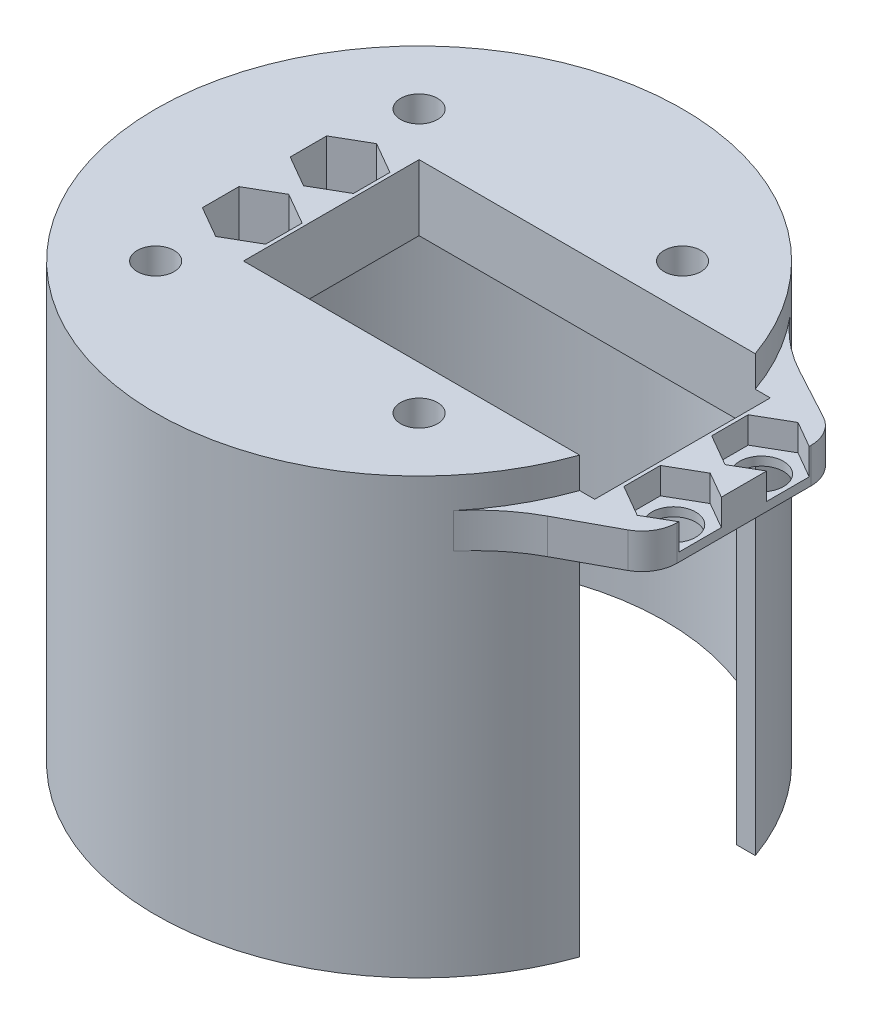
SolidWorks part; units mm, degrees
ref_plane "前视基准面" through (0, 0, 0) normal (0, 0, 1) x (1, 0, 0)
ref_plane "上视基准面" through (0, 0, 0) normal (0, 1, 0) x (1, 0, 0)
ref_plane "右视基准面" through (0, 0, 0) normal (1, 0, 0) x (0, 0, -1)
sketch "草图1" plane through (0, 0, 0) normal (0, 1, 0) x (1, 0, 0)
  line L0 (18.9568, 14.3477) -> (24.9021, 11.134)
  line L5 (-20, 10) -> (20, 10)
  line L6 (-20, 10) -> (-20, -10)
  line L11 (-20, -10) -> (20, -10)
  line L12 (20, 10) -> (20, -10)
  line L13 (-20, 10) -> (20, -10) construction
  line L14 (-20, -10) -> (20, 10) construction
  line L15 (-20, 10) -> (20, 10)
  line L17 (-27, -10) -> (20, -10)
  line L18 (27, 7.6152) -> (27, -7.6152)
  line L19 (-27, 10) -> (27, -10) construction
  line L20 (-27, -10) -> (27, 10) construction
  line L21 (-24, 5) -> (-21.5, 5)
  line L22 (-24, 5) -> (-24, 2.5)
  line L23 (-24, -5) -> (-21.5, -5)
  line L24 (24, 5) -> (24, -5)
  line L25 (-24, 5) -> (24, -5) construction
  line L26 (-24, -5) -> (-21.5525, -4.4901) construction
  line L27 (24.9021, -11.134) -> (18.9568, -14.3477)
  line L28 (21.5, 5) -> (24, 5)
  line L29 (21.5, -5) -> (24, -5)
  line L30 (-20, 5) -> (20, 5)
  line L31 (-24, -2.5) -> (-24, -5)
  line L32 (-20, -5) -> (20, -5)
  line L33 (-20, -4.1667) -> (24, 5) construction
  circle A0 centre (-10, 0) radius 10
  arc A1 (13.0803, 19.1651) -> (13.0803, -19.1651) centre (-10, 0) ccw
  circle A2 centre (24, 5) radius 2.5
  circle A3 centre (24, -5) radius 2.5
  circle A4 centre (-24, 5) radius 2.5
  circle A5 centre (-24, -5) radius 2.5
  arc A7 (18.2843, -10) -> (18.2843, 10) centre (-10, 0) ccw
  arc A8 (18.9568, -14.3477) -> (13.0803, -19.1651) centre (28.4671, -31.9418) ccw
  arc A9 (18.9568, 14.3477) -> (13.0803, 19.1651) centre (28.4671, 31.9418) cw
  arc A10 (24.9021, 11.134) -> (27, 7.6152) centre (23, 7.6152) cw
  arc A11 (24.9021, -11.134) -> (27, -7.6152) centre (23, -7.6152) ccw
  point P0 (0, 0)
  point P5 (-10, 0)
  point P9 (0, 0)
  point P14 (0, 0)
  dimension "D3" = 20
  dimension "D2" = 10
  dimension "D4" = 4
  dimension "D1" = 10
extrude "凸台-拉伸3" add sketch "草图1" along normal blind 4
sketch "草图10" plane through (0, 0, 0) normal (0, -1, 0) x (1, 0, 0)
  line L1 (20, 10) -> (-20, 10)
  line L2 (20, 10) -> (20, -10)
  line L3 (20, -10) -> (-20, -10)
  line L4 (-20, 10) -> (-20, -10)
  line L5 (20, 10) -> (-20, -10) construction
  line L6 (20, -10) -> (-20, 10) construction
  circle A0 centre (-10, 0) radius 30
  circle A1 centre (-10, 0) radius 28
  point P4 (0, 0)
  arc M35 (13.0803, 19.1651) -> (13.0803, -19.1651) centre (-10, 0) ccw
extrude "凸台-拉伸16" add sketch "草图10" along normal blind 42 contours A1 L1 A0 L3 M35
sketch "草图2" plane through (0, 4, 0) normal (0, 1, 0) x (1, 0, 0)
  line L0 (24, 0.8431) -> (27.6, 2.9215)
  line L1 (-24, 0.8431) -> (-20.4, 2.9215)
  line L2 (-20.4, 2.9215) -> (-20.4, 7.0785)
  line L3 (-20.4, 7.0785) -> (-24, 9.1569)
  line L4 (-24, 9.1569) -> (-27.6, 7.0785)
  line L5 (-27.6, 7.0785) -> (-27.6, 2.9215)
  line L6 (-27.6, 2.9215) -> (-24, 0.8431)
  line L7 (27.6, 2.9215) -> (27.6, 7.0785)
  line L8 (27.6, 7.0785) -> (24, 9.1569)
  line L9 (24, 9.1569) -> (20.4, 7.0785)
  line L10 (20.4, 7.0785) -> (20.4, 2.9215)
  line L11 (20.4, 2.9215) -> (24, 0.8431)
  line L12 (24, -9.1569) -> (27.6, -7.0785)
  line L13 (27.6, -7.0785) -> (27.6, -2.9215)
  line L14 (27.6, -2.9215) -> (24, -0.8431)
  line L15 (24, -0.8431) -> (20.4, -2.9215)
  line L16 (20.4, -2.9215) -> (20.4, -7.0785)
  line L17 (20.4, -7.0785) -> (24, -9.1569)
  line L18 (-24, -9.1569) -> (-20.4, -7.0785)
  line L19 (-20.4, -7.0785) -> (-20.4, -2.9215)
  line L20 (-20.4, -2.9215) -> (-24, -0.8431)
  line L21 (-24, -0.8431) -> (-27.6, -2.9215)
  line L22 (-27.6, -2.9215) -> (-27.6, -7.0785)
  line L23 (-27.6, -7.0785) -> (-24, -9.1569)
  circle A0 centre (-24, 5) radius 3.6 construction
  dimension "D1" = 2
  dimension "D2" = 2
extrude "切除-拉伸1" cut sketch "草图2" against normal blind 3
ref_plane "基准面2" through (-40, 0, 0) normal (-1, 0, 0) x (0, 0, 1)
sketch "草图3" plane through (0, 4, 0) normal (0, 1, 0) x (1, 0, 0)
  line L1 (-24, 0.8431) -> (-20.4, 2.9215)
  line L2 (-20.4, 2.9215) -> (-20.4, 7.0785)
  line L3 (-20.4, 7.0785) -> (-24, 9.1569)
  line L4 (-24, 9.1569) -> (-27.6, 7.0785)
  line L5 (-27.6, 7.0785) -> (-27.6, 2.9215)
  line L6 (-27.6, 2.9215) -> (-24, 0.8431)
  line L7 (-24, -9.1569) -> (-20.4, -7.0785)
  line L8 (-20.4, -7.0785) -> (-20.4, -2.9215)
  line L9 (-20.4, -2.9215) -> (-24, -0.8431)
  line L10 (-24, -0.8431) -> (-27.6, -2.9215)
  line L11 (-27.6, -2.9215) -> (-27.6, -7.0785)
  line L12 (-27.6, -7.0785) -> (-24, -9.1569)
  line L13 (-20, -10) -> (20, -10)
  line L14 (-20, -10) -> (-20, 10)
  line L15 (-20, 10) -> (20, 10)
  line L16 (20, -10) -> (20, 10)
  line L17 (-20, -10) -> (20, 10) construction
  line L18 (-20, 10) -> (20, -10) construction
  circle A0 centre (-10, 0) radius 30
  circle A1 centre (-24, 5) radius 3.6 construction
  circle A2 centre (-24, -5) radius 3.6 construction
  point P13 (0, 0)
  line M1 (-24, -9.1569) -> (-27.6, -7.0785)
  line M2 (-27.6, -7.0785) -> (-27.6, -2.9215)
  line M3 (-27.6, -2.9215) -> (-24, -0.8431)
  line M4 (-24, -0.8431) -> (-20.4, -2.9215)
  line M5 (-20.4, -2.9215) -> (-20.4, -7.0785)
  line M6 (-20.4, -7.0785) -> (-24, -9.1569)
  arc M18 (13.0803, 19.1651) -> (13.0803, -19.1651) centre (-10, 0) ccw
  line M27 (-24, 0.8431) -> (-27.6, 2.9215)
  line M28 (-27.6, 2.9215) -> (-27.6, 7.0785)
  line M29 (-27.6, 7.0785) -> (-24, 9.1569)
  line M30 (-24, 9.1569) -> (-20.4, 7.0785)
  line M31 (-20.4, 7.0785) -> (-20.4, 2.9215)
  line M32 (-20.4, 2.9215) -> (-24, 0.8431)
  line M34 (-20, -10) -> (-20, 10)
  line M35 (-20, 10) -> (20, 10)
extrude "凸台-拉伸4" add sketch "草图3" along normal blind 3.5 contours A0 L13 M18 M34 M35 M32 M27 M28 M29 M30 M31 M6 M1 M2 M3 M4 M5
sketch "草图4" plane through (0, 0, 0) normal (0, -1, 0) x (1, 0, 0)
  line L0 (9.1569, 15) -> (7.0785, 18.6)
  line L1 (-21.4, 15) -> (-20.8431, 15)
  line L5 (-22.4544, 12.4544) -> (2.3646, -12.3646) construction
  line L6 (-22.3646, -12.3646) -> (2.3646, 12.3646) construction
  line L7 (-20.8431, 15) -> (-22.9215, 18.6)
  line L8 (-22.9215, 18.6) -> (-27.0785, 18.6)
  line L9 (-27.0785, 18.6) -> (-29.1569, 15)
  line L10 (-29.1569, 15) -> (-27.0785, 11.4)
  line L11 (-27.0785, 11.4) -> (-22.9215, 11.4)
  line L12 (-22.9215, 11.4) -> (-20.8431, 15)
  line L13 (7.0785, 18.6) -> (2.9215, 18.6)
  line L14 (2.9215, 18.6) -> (0.8431, 15)
  line L15 (0.8431, 15) -> (2.9215, 11.4)
  line L16 (2.9215, 11.4) -> (7.0785, 11.4)
  line L17 (7.0785, 11.4) -> (9.1569, 15)
  line L18 (9.1569, -15) -> (7.0785, -11.4)
  line L19 (7.0785, -11.4) -> (2.9215, -11.4)
  line L20 (2.9215, -11.4) -> (0.8431, -15)
  line L21 (0.8431, -15) -> (2.9215, -18.6)
  line L22 (2.9215, -18.6) -> (7.0785, -18.6)
  line L23 (7.0785, -18.6) -> (9.1569, -15)
  line L24 (-20.8431, -15) -> (-22.9215, -11.4)
  line L25 (-22.9215, -11.4) -> (-27.0785, -11.4)
  line L26 (-27.0785, -11.4) -> (-29.1569, -15)
  line L27 (-29.1569, -15) -> (-27.0785, -18.6)
  line L28 (-27.0785, -18.6) -> (-22.9215, -18.6)
  line L29 (-22.9215, -18.6) -> (-20.8431, -15)
  circle A0 centre (-25, 15) radius 3.6 construction
  point P0 (-10, 0)
  point P1 (-10, 0)
  dimension "D1" = 2
  dimension "D2" = 2
extrude "切除-拉伸2" cut sketch "草图4" against normal blind 3
sketch "草图6" plane through (0, 0, 0) normal (0, -1, 0) x (1, 0, 0)
  line L1 (-25, 15) -> (5, 15)
  line L2 (-25, 15) -> (-25, -15)
  line L3 (-25, -15) -> (5, -15)
  line L4 (5, 15) -> (5, -15)
  line L5 (-25, 15) -> (5, -15) construction
  line L6 (-25, -15) -> (5, 15) construction
  circle A0 centre (-25, 15) radius 2.1
  circle A1 centre (5, 15) radius 2.1
  circle A2 centre (5, -15) radius 2.1
  circle A3 centre (-25, -15) radius 2.1
  point P0 (-10, 0)
  point P1 (-10, 0)
  point P17 (-10, 0)
  dimension "D1" = 4
extrude "切除-拉伸3" cut sketch "草图6" against normal through all contours A0 | A1 | A3 | A2
